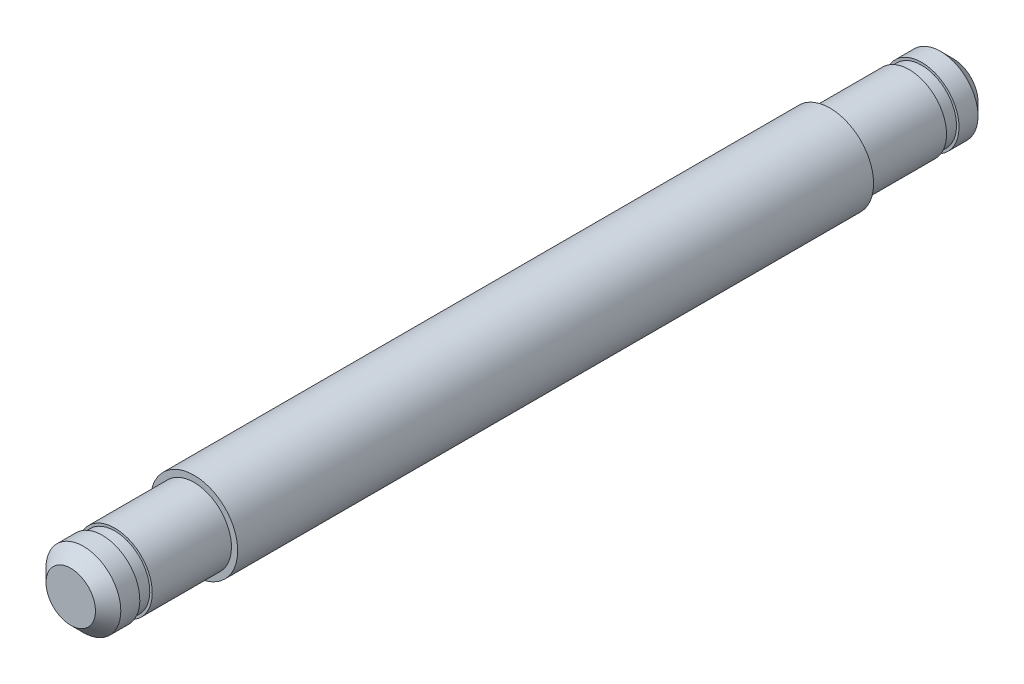
SolidWorks part; units mm, degrees
ref_plane "Front Plane" through (0, 0, 0) normal (0, 0, 1) x (1, 0, 0)
ref_plane "Top Plane" through (0, 0, 0) normal (0, 1, 0) x (1, 0, 0)
ref_plane "Right Plane" through (0, 0, 0) normal (1, 0, 0) x (0, 0, -1)
sketch "Sketch1" plane through (0, 0, 0) normal (1, 0, 0) x (0, 0, -1)
  line L0 (-0.683, 0) -> (-6.1274, 0) construction
  line L1 (-17.6958, 0) -> (-17.6958, 1.5)
  line L2 (-17.6958, 1.5) -> (-16.4258, 1.5)
  line L3 (-16.4258, 1.5) -> (-16.4258, 1.4)
  line L4 (-16.4258, 1.4) -> (-15.9258, 1.4)
  line L5 (-15.9258, 1.4) -> (-15.9258, 1.5)
  line L6 (-15.9258, 1.5) -> (-12.7508, 1.5)
  line L7 (-12.7508, 1.5) -> (-12.7508, 1.75)
  line L8 (-12.7508, 1.75) -> (0, 1.75)
  line L9 (0, 0) -> (0, 1.75)
  line L10 (-17.6958, 0) -> (0, 0)
  dimension "D1" = 3.5
  dimension "D2" = 12.7508
  dimension "D3" = 3.175
  dimension "D4" = 0.1
  dimension "D5" = 0.5
  dimension "D6" = 3
  dimension "D7" = 1.27
revolve "Revolve2" add sketch "Sketch1" angle 360 about L0
mirror "Mirror1" about plane through (0, 0, 0) normal (0, 0, 1) of "Revolve2"
chamfer "Chamfer1" distance 0.508 angle 45 2 edges at (0, 1.5, 17.6958) (0, 1.5, -17.6958)
